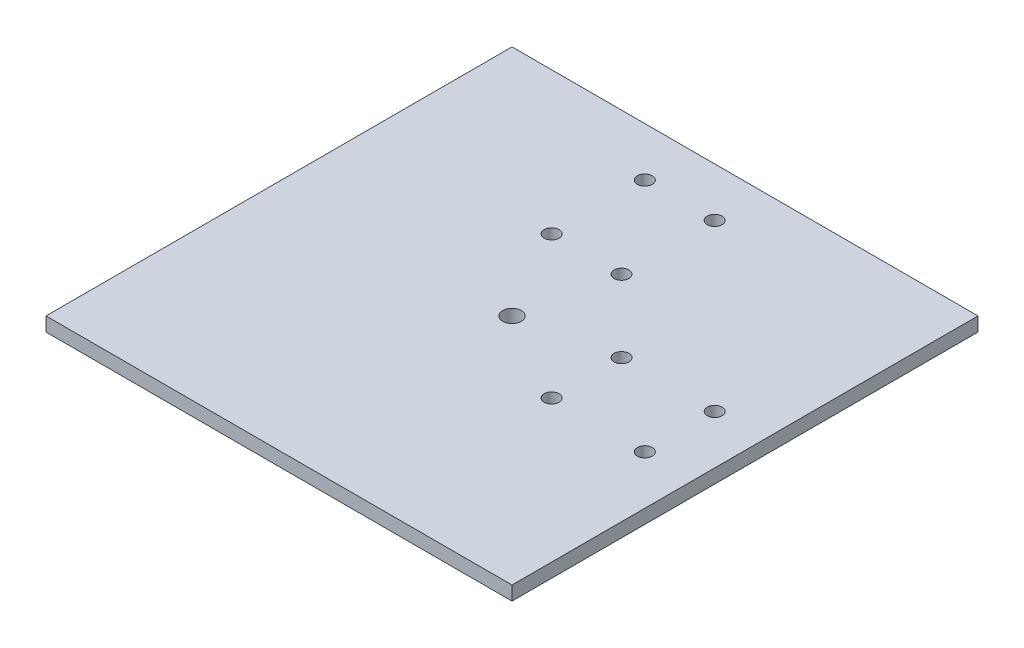
SolidWorks part; units mm, degrees
ref_plane "Front Plane" through (0, 0, 0) normal (0, 0, 1) x (1, 0, 0)
ref_plane "Top Plane" through (0, 0, 0) normal (0, 1, 0) x (1, 0, 0)
ref_plane "Right Plane" through (0, 0, 0) normal (1, 0, 0) x (0, 0, -1)
sketch "Sketch1" plane through (0, 0, 0) normal (0, 1, 0) x (1, 0, 0)
  line L0 (14, 16) -> (-21, 16)
  line L1 (-21, 16) -> (-21, 43)
  line L2 (-21, 43) -> (14, 43)
  line L3 (43, 14) -> (43, -21)
  line L4 (43, -21) -> (16, -21)
  line L5 (16, -21) -> (16, 14)
  line L6 (14, 16) -> (14, 43) construction
  line L7 (16, 14) -> (43, 14) construction
  line L8 (0, 0) -> (16, 16) construction
  point P4 (12.5307, 10.346)
  point P11 (0, 0)
  point P13 (18.7448, 16.7448)
  point P14 (19.6306, 17.6306)
  dimension "D1" = 27
  dimension "D2" = 37
  dimension "D3" = 2
  dimension "D4" = 2
  dimension "D5" = 45
  dimension "D6" = 16
sketch "Sketch2" plane through (0, 0, 0) normal (0, 1, 0) x (1, 0, 0)
  line L1 (50, -50) -> (-50, -50)
  line L2 (50, -50) -> (50, 50)
  line L3 (50, 50) -> (-50, 50)
  line L4 (-50, -50) -> (-50, 50)
  line L5 (50, -50) -> (-50, 50) construction
  line L6 (50, 50) -> (-50, -50) construction
  point P0 (0, 0)
  dimension "D1" = 100
extrude "Boss-Extrude1" add sketch "Sketch2" along normal blind 3
sketch "Carriage Hole Locations" plane through (0, 3, 0) normal (0, 1, 0) x (1, 0, 0)
  line L0 (0, 0) -> (0, 16) construction
  line L1 (14, 16) -> (-21, 16)
  line L2 (14, 16) -> (14, 43)
  line L3 (14, 43) -> (-21, 43)
  line L4 (-21, 16) -> (-21, 43)
  line L5 (14, 16) -> (-21, 43) construction
  line L6 (14, 43) -> (-21, 16) construction
  line L7 (43, -21) -> (16, -21)
  line L8 (43, -21) -> (43, 14)
  line L9 (43, 14) -> (16, 14)
  line L10 (16, -21) -> (16, 14)
  line L11 (43, -21) -> (16, 14) construction
  line L12 (43, 14) -> (16, -21) construction
  line L13 (16, 0) -> (0, 0) construction
  line L14 (14, 16) -> (16, 16) construction
  line L15 (16, 16) -> (16, 14) construction
  line L17 (4, 19.5) -> (-11, 19.5)
  line L18 (4, 19.5) -> (4, 39.5)
  line L19 (4, 39.5) -> (-11, 39.5)
  line L20 (-11, 19.5) -> (-11, 39.5)
  line L21 (4, 19.5) -> (-11, 39.5) construction
  line L22 (4, 39.5) -> (-11, 19.5) construction
  line L23 (39.5, -11) -> (19.5, -11)
  line L24 (39.5, -11) -> (39.5, 4)
  line L25 (39.5, 4) -> (19.5, 4)
  line L26 (19.5, -11) -> (19.5, 4)
  line L27 (39.5, -11) -> (19.5, 4) construction
  line L28 (39.5, 4) -> (19.5, -11) construction
  point P0 (-3.5, 29.5)
  point P5 (29.5, -3.5)
  point P15 (-3.5, 29.5)
  point P21 (29.5, -3.5)
  dimension "D1" = 27
  dimension "D2" = 35
  dimension "D3" = 16
  dimension "D4" = 2
  dimension "D5" = 20
  dimension "D6" = 15
sketch "Sketch8" plane through (0, 0, 0) normal (0, -1, 0) x (1, 0, 0)
  circle A0 centre (-11, -19.5) radius 3
  circle A1 centre (4, -19.5) radius 3
  circle A2 centre (4, -39.5) radius 3
  circle A3 centre (-11, -39.5) radius 3
  dimension "D1" = 6
extrude "Boss-Extrude2" add sketch "Sketch8" along normal blind 15.1
hole_wizard "M3 Clearance Hole1" positions "Sketch4" profile "Sketch5" hole size "M3" standard "ANSI Metric" end condition through all
sketch "Sketch4" plane through (0, 3, 0) normal (0, 1, 0) x (1, 0, 0)
  point P0 (-11, 39.5)
  point P3 (4, 39.5)
  point P6 (4, 19.5)
  point P9 (-11, 19.5)
  point P12 (19.5, 4)
  point P15 (39.5, 4)
  point P18 (39.5, -11)
  point P21 (19.5, -11)
sketch "Sketch5" plane through (-11, 3, -39.5) normal (1, 0, 0) x (0, 0, 1)
  line L0 (0, 0) -> (0, 18.1)
  line L1 (0, 18.1) -> (1.6, 18.1)
  line L2 (1.6, 18.1) -> (1.6, 0)
  line L5 (1.6, 0) -> (0, 0)
  line L11 (0, -6.35) -> (0, 107.95) construction
  dimension "Thru Hole Dia." = 3.2
  dimension "Thru Hole Depth" = 18.1
hole_wizard "Ø4.0 (4) Diameter Hole1" positions "Sketch6" profile "Sketch7" hole size "Ø4.0" standard "ANSI Metric" end condition through all
sketch "Sketch6" plane through (0, 3, 0) normal (0, 1, 0) x (1, 0, 0)
  point P0 (0, 0)
sketch "Sketch7" plane through (0, 3, 0) normal (1, 0, 0) x (0, 0, 1)
  line L0 (0, 0) -> (0, 18.1)
  line L1 (0, 18.1) -> (2, 18.1)
  line L2 (2, 18.1) -> (2, 0)
  line L5 (2, 0) -> (0, 0)
  line L11 (0, -6.35) -> (0, 107.95) construction
  dimension "Thru Hole Dia." = 4
  dimension "Thru Hole Depth" = 18.1
